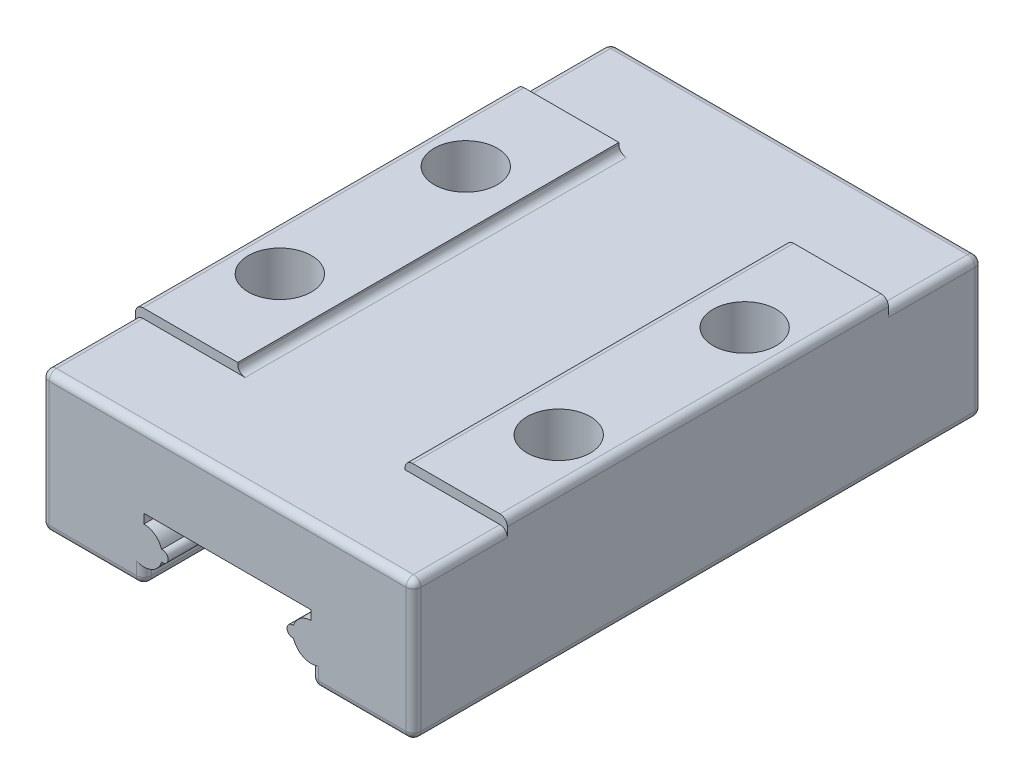
SolidWorks part; units mm, degrees
ref_plane "Front Plane" through (0, 0, 0) normal (0, 0, 1) x (1, 0, 0)
ref_plane "Top Plane" through (0, 0, 0) normal (0, 1, 0) x (1, 0, 0)
ref_plane "Right Plane" through (0, 0, 0) normal (1, 0, 0) x (0, 0, -1)
sketch "Sketch1" plane through (0, 0, 0) normal (0, 0, 1) x (1, 0, 0)
  line L0 (-4.5, 2.75) -> (-4.5, 1.25)
  line L1 (-4.5, -2.75) -> (4.5, -2.75)
  line L2 (-4.5, -2.75) -> (-4.5, 2.75)
  line L3 (-4.5, 2.75) -> (4.5, 2.75)
  line L4 (4.5, -2.75) -> (4.5, 2.75)
  line L5 (-4.5, -2.75) -> (4.5, 2.75) construction
  line L6 (-4.5, 2.75) -> (4.5, -2.75) construction
  line L7 (0, 2.75) -> (0, -3.4858) construction
  line L8 (-10, -2.75) -> (10, -2.75)
  line L10 (-10, -2.75) -> (10, -2.75)
  line L11 (-10, -2.75) -> (-10, 7.25)
  line L12 (-10, 7.25) -> (10, 7.25)
  line L13 (10, -2.75) -> (10, 7.25)
  line L14 (-10, 7.25) -> (10, 7.25)
  line L15 (-10, 7.25) -> (-10, -0.75)
  line L16 (-10, -0.75) -> (10, -0.75)
  line L17 (10, 7.25) -> (10, -0.75)
  circle A0 centre (-4.5, 1.25) radius 1
  circle A1 centre (4.5, 1.25) radius 1
  circle A2 centre (-3.5, 1.25) radius 0.3
  circle A3 centre (3.5, 1.25) radius 0.3
  point P0 (0, 0)
  point P18 (0, -2.75)
  dimension "D2" = 2
  dimension "D3" = 0.6
  dimension "D10" = 2
  dimension "D11" = 0.6
  dimension "D1" = 1.5
  dimension "D4" = 20
  dimension "D5" = 5.5
  dimension "D6" = 0
  dimension "D7" = 6.2358
  dimension "D8" = 9
  dimension "D9" = 0
  dimension "D12" = 0
  dimension "D13" = 1
  dimension "D14" = 1.5
  dimension "D15" = 1.5
  dimension "D16" = 10
  dimension "D17" = 20
  dimension "D18" = 8
extrude "Boss-Extrude1" add sketch "Sketch1" along normal blind 30.6 contours L4 A1 L16 L13 L12 L11 L2 A0 L0 L3 | L2 A0 | A2 A0 L2 | A0 A2 | A0 A2 | A3 A1 | A3 A1 | A1 A3 L4 | A1 L4
sketch "Sketch2" plane through (0, 7.25, 0) normal (0, 1, 0) x (1, 0, 0)
  line L0 (-10, -15.3) -> (10, -15.3) construction
  line L1 (10, -30.6) -> (10, 0) construction
  line L2 (-10, -25.55) -> (10, -25.55)
  line L3 (-10, -25.55) -> (-10, -5.05)
  line L4 (-10, -5.05) -> (10, -5.05)
  line L5 (10, -25.55) -> (10, -5.05)
  line L6 (-10, -25.55) -> (10, -5.05) construction
  line L7 (-10, -5.05) -> (10, -25.55) construction
  line L11 (-10, -25.55) -> (10, -25.55)
  line L12 (-10, -25.55) -> (-10, -30.6)
  line L13 (-10, -30.6) -> (10, -30.6)
  line L14 (10, -25.55) -> (10, -30.6)
  line L15 (-10, -5.05) -> (10, -5.05)
  line L16 (-10, -5.05) -> (-10, 0)
  line L17 (-10, 0) -> (10, 0)
  line L18 (10, -5.05) -> (10, 0)
  point P1 (0, -15.3)
  line M3 (10, 0) -> (-10, 0)
  line M4 (-10, 0) -> (-10, -30.6)
  line M5 (-10, -30.6) -> (10, -30.6)
  line M6 (10, -30.6) -> (10, 0)
  dimension "D1" = 20.5
  dimension "D2" = 20
extrude "Cut-Extrude1" cut sketch "Sketch2" against normal blind 0.5 contours L4 M4 M6 M3 | L2 M4 M5 M6
sketch "Sketch4" plane through (0, 0, 25.55) normal (0, 0, 1) x (1, 0, 0)
  line L0 (10, -0.75) -> (10, 6.75) construction
  line L1 (10, 6.75) -> (-10, 6.75) construction
  line L2 (-10, 6.75) -> (-10, -0.75) construction
  line L3 (-10, -0.75) -> (-4.5, -0.75) construction
  line L4 (-4.5, -0.75) -> (-4.5, 0.25) construction
  line L5 (-4.5, 2.25) -> (-4.5, 2.75) construction
  line L6 (-4.5, 2.75) -> (4.5, 2.75) construction
  line L7 (4.5, 2.75) -> (4.5, 2.25) construction
  line L8 (4.5, 0.25) -> (4.5, -0.75) construction
  line L9 (4.5, -0.75) -> (10, -0.75) construction
  line L10 (10, 7.25) -> (-10, 7.25) construction
  line L11 (-10, 7.25) -> (-10, 6.75) construction
  line L12 (-10, 6.75) -> (10, 6.75) construction
  line L13 (10, 6.75) -> (10, 7.25) construction
  line L14 (10, -0.75) -> (10, 6.75)
  line L15 (10, 6.75) -> (-10, 6.75)
  line L16 (-10, 6.75) -> (-10, -0.75)
  line L17 (-10, -0.75) -> (-4.5, -0.75)
  line L18 (-4.5, -0.75) -> (-4.5, 0.25)
  line L19 (-4.5, 2.25) -> (-4.5, 2.75)
  line L20 (-4.5, 2.75) -> (4.5, 2.75)
  line L21 (4.5, 2.75) -> (4.5, 2.25)
  line L22 (4.5, 0.25) -> (4.5, -0.75)
  line L23 (4.5, -0.75) -> (10, -0.75)
  line L24 (10, 7.25) -> (-10, 7.25)
  line L25 (-10, 7.25) -> (-10, 6.75)
  line L26 (-10, 6.75) -> (10, 6.75)
  line L27 (10, 6.75) -> (10, 7.25)
  line L28 (0, 0) -> (0, 7.25)
  line L29 (0, 6.75) -> (4.5, 6.75)
  line L31 (4.5, 6.75) -> (-4.5, 6.75)
  line L32 (4.5, 6.75) -> (4.5, 7.25)
  line L33 (4.5, 7.25) -> (-4.5, 7.25)
  line L34 (-4.5, 6.75) -> (-4.5, 7.25)
  arc A0 (-4.5, 0.25) -> (-3.545, 0.9534) centre (-4.5, 1.25) ccw construction
  arc A1 (-3.545, 0.9534) -> (-3.545, 1.5466) centre (-3.5, 1.25) ccw construction
  arc A2 (-3.545, 1.5466) -> (-4.5, 2.25) centre (-4.5, 1.25) ccw construction
  arc A3 (4.5, 2.25) -> (3.545, 1.5466) centre (4.5, 1.25) ccw construction
  arc A4 (3.545, 1.5466) -> (3.545, 0.9534) centre (3.5, 1.25) ccw construction
  arc A5 (3.545, 0.9534) -> (4.5, 0.25) centre (4.5, 1.25) ccw construction
  arc A6 (-4.5, 0.25) -> (-3.545, 0.9534) centre (-4.5, 1.25) ccw
  arc A7 (-3.545, 0.9534) -> (-3.545, 1.5466) centre (-3.5, 1.25) ccw
  arc A8 (-3.545, 1.5466) -> (-4.5, 2.25) centre (-4.5, 1.25) ccw
  arc A9 (4.5, 2.25) -> (3.545, 1.5466) centre (4.5, 1.25) ccw
  arc A10 (3.545, 1.5466) -> (3.545, 0.9534) centre (3.5, 1.25) ccw
  arc A11 (3.545, 0.9534) -> (4.5, 0.25) centre (4.5, 1.25) ccw
  dimension "D1" = 9
extrude "Cut-Extrude2" cut sketch "Sketch4" against normal blind 21.5 contours L34 L26 L28 L24 | L26 L32 L24 L28
sketch "Sketch5" plane through (0, 7.25, 0) normal (0, 1, 0) x (1, 0, 0)
  line L0 (0, -30.5738) -> (0, 0)
  line L1 (0, -15.2869) -> (14.7145, -15.2869) construction
  line L3 (-7.5, -20.2869) -> (7.5, -20.2869)
  line L4 (-7.5, -20.2869) -> (-7.5, -10.2869)
  line L5 (-7.5, -10.2869) -> (7.5, -10.2869)
  line L6 (7.5, -20.2869) -> (7.5, -10.2869)
  line L7 (-7.5, -20.2869) -> (7.5, -10.2869) construction
  line L8 (-7.5, -10.2869) -> (7.5, -20.2869) construction
  circle A0 centre (7.5, -10.2869) radius 1.7
  circle A1 centre (7.5, -20.2869) radius 1.7
  circle A2 centre (-7.5, -10.2869) radius 1.7
  circle A3 centre (-7.5, -20.2869) radius 1.7
  point P10 (0, -15.2869)
  dimension "D3" = 3.4
  dimension "D1" = 10
  dimension "D2" = 15
  dimension "D4" = 30.5738
  dimension "D5" = 0
extrude "Cut-Extrude3" cut sketch "Sketch5" against normal blind 3 contours L4 A3 L3 | L3 A3 L4 | A1 L6 L3 | A1 L3 L6 | L6 A0 L5 | L5 A0 L6 | A2
fillet "Fillet1" radius 0.4 12 edges at (4.5, -0.75, 15.3) (10, -0.75, 15.3) (-4.5, -0.75, 15.3) (-10, -0.75, 15.3) (10, 6.75, 2.525) (10, 7.25, 15.3) (-10, 6.75, 2.525) (-10, 7.25, 15.3) (10, 6.75, 28.075) (-10, 6.75, 28.075) (-4.5, 6.75, 15.3) (4.5, 7.25, 15.3)
fillet "Fillet2" radius 0.4 26 edges at (4.5, -0.05, 0) (4.5, -0.05, 30.6) (4.6172, -0.6328, 30.6) (4.6172, -0.6328, 0) (7.25, -0.75, 30.6) (7.25, -0.75, 0) (9.8828, -0.6328, 30.6) (9.8828, -0.6328, 0) (10, 3, 0) (9.8828, 6.6328, 0) (-4.5, -0.05, 30.6) (-4.5, -0.05, 0) (-4.6172, -0.6328, 30.6) (-4.6172, -0.6328, 0) (-7.25, -0.75, 0) (-7.25, -0.75, 30.6) (-9.8828, -0.6328, 30.6) (-9.8828, -0.6328, 0) (-10, 3, 0) (-9.8828, 6.6328, 0) (-10, 3, 30.6) (-9.8828, 6.6328, 30.6) (10, 3, 30.6) (9.8828, 6.6328, 30.6) (0, 6.75, 0) (0, 6.75, 30.6)
